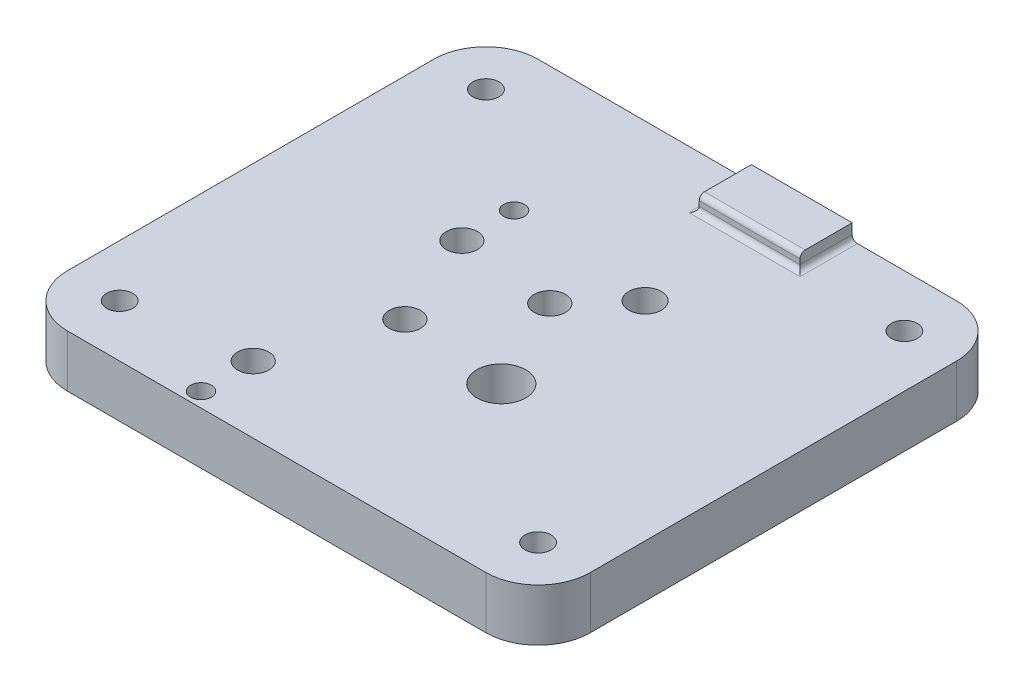
SolidWorks part; units mm, degrees
ref_plane "Front" through (0, 0, 0) normal (0, 0, 1) x (1, 0, 0)
ref_plane "Top" through (0, 0, 0) normal (0, 1, 0) x (1, 0, 0)
ref_plane "Right" through (0, 0, 0) normal (1, 0, 0) x (0, 0, -1)
sketch "Sketch2" plane through (0, 0, 0) normal (0, 1, 0) x (1, 0, 0)
  line L0 (114.3, 127) -> (190.5, 76.2)
  line L1 (114.3, -127) -> (-114.3, -127)
  line L2 (190.5, -76.2) -> (190.5, 76.2)
  line L3 (114.3, 127) -> (-114.3, 127)
  line L4 (-190.5, -76.2) -> (-190.5, 76.2)
  line L5 (190.5, -127) -> (-190.5, 127) construction
  line L6 (190.5, 127) -> (-190.5, -127) construction
  line L7 (190.5, -76.2) -> (114.3, -127)
  line L8 (-114.3, 127) -> (-190.5, 76.2)
  line L9 (-190.5, -76.2) -> (-114.3, -127)
  point P0 (0, 0)
  dimension "D1" = 254
  dimension "D2" = 381
  dimension "D3" = 50.8
  dimension "D4" = 76.2
  dimension "D5" = 76.2
  dimension "D6" = 50.8
  dimension "D7" = 50.8
  dimension "D8" = 76.2
  dimension "D9" = 50.8
  dimension "D10" = 76.2
  dimension "D11" = 228.6
extrude "Boss-Extrude1" add sketch "Sketch2" along normal mid plane 25.4 contours L3 L8 L4 L9 L1 L7 L2 L0
sketch "Sketch5" plane through (0, 12.7, 0) normal (0, 1, 0) x (1, 0, 0)
  circle A0 centre (11.9471, 32.7124) radius 7.9375
  line B0 (-988.0529, -37.29) -> (49011.9471, -37.29) construction
  line B1 (11.9471, -1037.29) -> (11.9471, 48962.71) construction
  circle B2 centre (11.9471, -37.29) radius 25.0063
  circle B3 centre (11.9471, -37.29) radius 11.9126
  arc B4 (29.8046, 15.2073) -> (-12.1051, 39.5537) centre (11.9471, 32.7124) ccw
  arc B5 (29.8046, 15.2073) -> (29.8046, -19.785) centre (47.653, -2.2888) ccw
  arc B6 (-62.9039, -5.1545) -> (-35.018, -60.2135) centre (-58.0553, -37.29) ccw
  arc B7 (-2.6807, -57.5716) -> (-35.018, -60.2135) centre (-17.3011, -77.8429) ccw
  circle B8 centre (-58.0553, -37.29) radius 7.9375
  arc B9 (11.9471, 32.7124) -> (-58.0553, -37.29) centre (11.9471, -37.29) ccw construction
  arc B10 (-62.9039, -5.1545) -> (-12.1051, 39.5537) centre (-72.2297, 56.6554) ccw
  circle B11 centre (11.9471, 32.7124) radius 5.9563
  dimension "D1" = 15.875
sketch_block_instance "Block-block-1"
sketch_block "Block1" parameters "D1"=50.0126, "D2"=23.8252, "D3"=50.0126, "D4"=49.9872, "D6"=15.875, "D7"=64.9986, "D8"=49.9872, "D9"=125.0188, "D10"=11.9126, "D5"=70.0024
extrude "Cut-Extrude3" cut sketch "Sketch5" against normal through all contours B3 | A0 B11 | B11
sketch "Sketch6" plane through (0, 12.7, 0) normal (0, 1, 0) x (1, 0, 0)
  line L0 (-30.9314, 9.7311) -> (-153.4869, 148.9822) construction
  line L1 (-141.3546, 108.5187) -> (113.1534, 108.5187)
  line L2 (-141.3546, 108.5187) -> (-141.3546, -120.5893)
  line L3 (-141.3546, -120.5893) -> (113.1534, -120.5893)
  line L4 (113.1534, 108.5187) -> (113.1534, -120.5893)
  line L5 (-153.4869, 148.9822) -> (111.8664, -152.52) construction
  line L6 (11.9471, -37.29) -> (11.9471, 142.185) construction
  line L7 (11.9471, 142.185) -> (11.9471, -141.8142) construction
  line L8 (-58.0553, -37.29) -> (-206.7494, -37.29) construction
  line L9 (-206.7494, -37.29) -> (209.5432, -37.29) construction
  line L10 (-115.9546, 108.5187) -> (-141.3546, 83.1187)
  line L11 (87.7534, 108.5187) -> (113.1534, 83.1187)
  line L12 (-141.3546, -95.1893) -> (-115.9546, -120.5893)
  line L13 (113.1534, -95.1893) -> (87.7534, -120.5893)
  line L14 (114.3, 127) -> (-114.3, 127) construction
  line L15 (114.3, 127) -> (190.5, 76.2) construction
  line L16 (190.5, -76.2) -> (190.5, 76.2) construction
  line L17 (190.5, -76.2) -> (114.3, -127) construction
  line L18 (114.3, -127) -> (-114.3, -127) construction
  line L19 (-190.5, -76.2) -> (-114.3, -127) construction
  line L20 (-190.5, -76.2) -> (-190.5, 76.2) construction
  line L21 (-114.3, 127) -> (-190.5, 76.2) construction
  line L22 (114.3, 127) -> (-114.3, 127)
  line L23 (114.3, 127) -> (190.5, 76.2)
  line L24 (190.5, -76.2) -> (190.5, 76.2)
  line L25 (190.5, -76.2) -> (114.3, -127)
  line L26 (114.3, -127) -> (-114.3, -127)
  line L27 (-190.5, -76.2) -> (-114.3, -127)
  line L28 (-190.5, -76.2) -> (-190.5, 76.2)
  line L29 (-114.3, 127) -> (-190.5, 76.2)
  arc A0 (29.8046, 15.2073) -> (29.8046, -19.785) centre (47.653, -2.2888) ccw construction
  arc A1 (29.8046, 15.2073) -> (-12.1051, 39.5537) centre (11.9471, 32.7124) ccw construction
  arc A2 (-62.9039, -5.1545) -> (-12.1051, 39.5537) centre (-72.2297, 56.6554) ccw construction
  arc A3 (-62.9039, -5.1545) -> (-35.018, -60.2135) centre (-58.0553, -37.29) ccw construction
  arc A4 (-2.6807, -57.5716) -> (-35.018, -60.2135) centre (-17.3011, -77.8429) ccw construction
  circle A5 centre (11.9471, -37.29) radius 11.9126 construction
  circle A6 centre (11.9471, -37.29) radius 25.0063 construction
  circle A7 centre (11.9471, 32.7124) radius 5.9563 construction
  circle A8 centre (-58.0553, -37.29) radius 7.9375 construction
  arc A9 (29.8046, 15.2073) -> (29.8046, -19.785) centre (47.653, -2.2888) ccw
  arc A10 (29.8046, 15.2073) -> (-12.1051, 39.5537) centre (11.9471, 32.7124) ccw
  arc A11 (-62.9039, -5.1545) -> (-12.1051, 39.5537) centre (-72.2297, 56.6554) ccw
  arc A12 (-62.9039, -5.1545) -> (-35.018, -60.2135) centre (-58.0553, -37.29) ccw
  arc A13 (-2.6807, -57.5716) -> (-35.018, -60.2135) centre (-17.3011, -77.8429) ccw
  circle A14 centre (11.9471, -37.29) radius 11.9126
  circle A15 centre (11.9471, -37.29) radius 25.0063
  circle A16 centre (11.9471, 32.7124) radius 5.9563
  circle A17 centre (-58.0553, -37.29) radius 7.9375
  point P26 (11.9471, 57.7187)
  point P32 (-90.5546, -37.29)
  point P33 (-58.0553, -69.7893)
  point P34 (36.9534, 32.7124)
  line M10 (190.5, 76.2) -> (114.3, 127)
  line M11 (114.3, 127) -> (-114.3, 127)
  line M12 (-114.3, 127) -> (-190.5, 76.2)
  line M13 (-190.5, 76.2) -> (-190.5, -76.2)
  line M14 (-190.5, -76.2) -> (-114.3, -127)
  line M15 (-114.3, -127) -> (114.3, -127)
  line M16 (114.3, -127) -> (190.5, -76.2)
  line M17 (190.5, -76.2) -> (190.5, 76.2)
  dimension "D1" = 50.8
  dimension "D2" = 50.8
  dimension "D3" = 76.2
  dimension "D4" = 50.8
  dimension "D5" = 25.4
  dimension "D6" = 25.4
  dimension "D7" = 25.4
  dimension "D8" = 25.4
  dimension "D9" = 25.4
  dimension "D10" = 25.4
  dimension "D11" = 25.4
  dimension "D12" = 25.4
extrude "Cut-Extrude4" cut sketch "Sketch6" against normal through all contours L1 L4 L3 L2 M17 M10 M11 M12 M13 M14 M15 M16 | L1 L11 L4 | L10 L1 L2 | L12 L2 L3 | L4 L13 L3
sketch "Sketch7" plane through (0, -12.7, 0) normal (0, -1, 0) x (1, 0, 0)
  line L7 (100.4534, 89.9288) -> (82.4929, 107.8893)
  line L9 (100.4534, 89.9288) -> (82.4929, 107.8893)
  line L12 (82.4929, 107.8893) -> (-110.6941, 107.8893)
  line L14 (-110.6941, 107.8893) -> (-128.6546, 89.9288)
  line L15 (-110.6941, 107.8893) -> (-128.6546, 89.9288)
  line L16 (-115.9546, 120.5893) -> (87.7534, 120.5893) construction
  line L17 (82.4929, 107.8893) -> (-110.6941, 107.8893)
  line L18 (-141.3546, -83.1187) -> (-141.3546, 95.1893) construction
  line L19 (113.1534, -83.1187) -> (113.1534, 95.1893) construction
  line L20 (-115.9546, -108.5187) -> (87.7534, -108.5187) construction
  line L24 (-128.6546, 89.9288) -> (-128.6546, -77.8581)
  line L25 (-128.6546, -77.8581) -> (-110.6941, -95.8187)
  line L26 (-110.6941, -95.8187) -> (82.4929, -95.8187)
  line L27 (82.4929, -95.8187) -> (100.4534, -77.8581)
  line L28 (100.4534, -77.8581) -> (100.4534, 89.9288)
  line L32 (-128.6546, 89.9288) -> (-128.6546, -77.8581)
  line L33 (-128.6546, -77.8581) -> (-110.6941, -95.8187)
  line L34 (-110.6941, -95.8187) -> (82.4929, -95.8187)
  line L35 (82.4929, -95.8187) -> (100.4534, -77.8581)
  line L36 (100.4534, -77.8581) -> (100.4534, 89.9288)
  circle A0 centre (87.7534, 95.1893) radius 12.7
  circle A1 centre (-115.9546, 95.1893) radius 12.7
  circle A2 centre (87.7534, -83.1187) radius 12.7
  circle A3 centre (-115.9546, -83.1187) radius 12.7
  point P0 (-115.9546, 95.1893)
  point P1 (87.7534, 95.1893)
  point P3 (87.7534, -83.1187)
  point P4 (-115.9546, -83.1187)
  dimension "D10" = 25.4
  dimension "D11" = 25.4
  dimension "D12" = 25.4
  dimension "D13" = 25.4
  dimension "D2" = 25.4
  dimension "D3" = 25.4
  dimension "D4" = 25.4
  dimension "D5" = 25.4
  dimension "D6" = 25.4
  dimension "D7" = 25.4
  dimension "D8" = 25.4
  dimension "D9" = 25.4
  dimension "D1" = 12.7
extrude "Cut-Extrude5" cut sketch "Sketch7" against normal blind 7.5057 contours L9 A0 | L9 A0 | L15 A1 | L15 A1 | L35 A2 | L35 A2 | L33 A3 | L33 A3
sketch "Sketch8" plane through (0, -5.1943, 0) normal (0, -1, 0) x (1, 0, 0)
  circle A0 centre (-115.9546, 95.1893) radius 6.35
  circle A1 centre (87.7534, 95.1893) radius 6.35
  circle A2 centre (87.7534, -83.1187) radius 6.35
  circle A3 centre (-115.9546, -83.1187) radius 6.35
  dimension "D1" = 12.7
  dimension "D2" = 12.7
  dimension "D3" = 12.7
  dimension "D4" = 12.7
extrude "Cut-Extrude6" cut sketch "Sketch8" against normal through all contours A0 | A1 | A3 | A2
sketch "Sketch9" plane through (0, 12.7, 0) normal (0, 1, 0) x (1, 0, 0)
  line L0 (-115.9546, 108.5187) -> (-141.3546, 83.1187) construction
  line L1 (-141.3546, 83.1187) -> (-141.3546, -95.1893) construction
  line L2 (-141.3546, -95.1893) -> (-115.9546, -120.5893) construction
  line L3 (-115.9546, -120.5893) -> (87.7534, -120.5893) construction
  line L4 (113.1534, -95.1893) -> (87.7534, -120.5893) construction
  line L5 (113.1534, 83.1187) -> (113.1534, -95.1893) construction
  line L6 (87.7534, 108.5187) -> (113.1534, 83.1187) construction
  line L7 (-115.9546, 108.5187) -> (87.7534, 108.5187) construction
  line L8 (-115.9546, 108.5187) -> (-141.3546, 83.1187)
  line L9 (-141.3546, 83.1187) -> (-141.3546, -95.1893)
  line L10 (-141.3546, -95.1893) -> (-115.9546, -120.5893)
  line L11 (-115.9546, -120.5893) -> (87.7534, -120.5893)
  line L12 (113.1534, -95.1893) -> (87.7534, -120.5893)
  line L13 (113.1534, 83.1187) -> (113.1534, -95.1893)
  line L14 (87.7534, 108.5187) -> (113.1534, 83.1187)
  line L15 (-115.9546, 108.5187) -> (87.7534, 108.5187)
  arc A0 (-115.9546, 108.5187) -> (-141.3546, 83.1187) centre (-115.9546, 83.1187) ccw
  arc A1 (-115.9546, -120.5893) -> (-141.3546, -95.1893) centre (-115.9546, -95.1893) cw
  arc A2 (87.7534, -120.5893) -> (113.1534, -95.1893) centre (87.7534, -95.1893) ccw
  arc A3 (113.1534, 83.1187) -> (87.7534, 108.5187) centre (87.7534, 83.1187) ccw
  line M20 (-115.9546, 108.5187) -> (-141.3546, 83.1187)
  line M22 (-141.3546, -95.1893) -> (-115.9546, -120.5893)
  line M24 (87.7534, -120.5893) -> (113.1534, -95.1893)
  line M26 (113.1534, 83.1187) -> (87.7534, 108.5187)
  dimension "D1" = 25.4
extrude "Boss-Extrude2" add sketch "Sketch9" against normal blind 25.4 contours A3 M26 | A0 M20 | A1 M22 | A2 M24
sketch "Sketch10" plane through (0, 12.7, 0) normal (0, 1, 0) x (1, 0, 0)
  line L0 (-12.1051, 39.5537) -> (-12.1051, 108.5187) construction
  line L1 (-115.9546, 108.5187) -> (87.7534, 108.5187) construction
  line L2 (36.9534, 32.7124) -> (36.9534, 108.5187) construction
  line L3 (-62.9039, -5.1545) -> (-141.3546, -6.0353) construction
  line L4 (-141.3546, 83.1187) -> (-141.3546, -95.1893) construction
  line L5 (-58.0553, -69.7893) -> (-141.3546, -69.7893) construction
  line L6 (11.9471, 32.7124) -> (11.9471, 108.5187) construction
  line L7 (-19.9299, 108.5187) -> (-19.9299, 39.5537) construction
  line L8 (43.9511, 108.5187) -> (43.9511, 32.7124) construction
  line L10 (-12.1051, 108.5187) -> (36.9534, 108.5187)
  line L11 (-12.1051, 108.5187) -> (-12.1051, 83.1187)
  line L12 (-12.1051, 83.1187) -> (36.9534, 83.1187)
  line L13 (36.9534, 108.5187) -> (36.9534, 83.1187)
  arc A0 (29.8046, 15.2073) -> (29.8046, -19.785) centre (47.653, -2.2888) ccw construction
  arc A1 (29.8046, 15.2073) -> (-12.1051, 39.5537) centre (11.9471, 32.7124) ccw construction
  arc A2 (-62.9039, -5.1545) -> (-12.1051, 39.5537) centre (-72.2297, 56.6554) ccw construction
  arc A3 (-62.9039, -5.1545) -> (-35.018, -60.2135) centre (-58.0553, -37.29) ccw construction
  arc A4 (-2.6807, -57.5716) -> (-35.018, -60.2135) centre (-17.3011, -77.8429) ccw construction
  circle A5 centre (11.9471, -37.29) radius 11.9126 construction
  circle A6 centre (11.9471, -37.29) radius 25.0063 construction
  circle A7 centre (11.9471, 32.7124) radius 5.9563 construction
  circle A8 centre (-58.0553, -37.29) radius 7.9375 construction
  arc A9 (29.8046, 15.2073) -> (29.8046, -19.785) centre (47.653, -2.2888) ccw
  arc A10 (29.8046, 15.2073) -> (-12.1051, 39.5537) centre (11.9471, 32.7124) ccw
  arc A11 (-62.9039, -5.1545) -> (-12.1051, 39.5537) centre (-72.2297, 56.6554) ccw
  arc A12 (-62.9039, -5.1545) -> (-35.018, -60.2135) centre (-58.0553, -37.29) ccw
  arc A13 (-2.6807, -57.5716) -> (-35.018, -60.2135) centre (-17.3011, -77.8429) ccw
  circle A14 centre (11.9471, -37.29) radius 11.9126
  circle A15 centre (11.9471, -37.29) radius 25.0063
  circle A16 centre (11.9471, 32.7124) radius 5.9563
  circle A17 centre (-58.0553, -37.29) radius 7.9375
  line M10 (87.7534, 108.5187) -> (-115.9546, 108.5187)
  dimension "D1" = 31.877
  dimension "D2" = 32.004
  dimension "D3" = 25.4
  dimension "D4" = 49.0586
extrude "Boss-Extrude3" add sketch "Sketch10" along normal blind 7.493 contours L13 L11 L12 M10
fillet "Fillet1" radius 2.54 4 edges at (12.4242, 12.7, -83.1187) (12.4242, 20.193, -83.1187) (36.9534, 12.7, -95.8187) (-12.1051, 12.7, -95.8187)
sketch "Sketch11" plane through (0, 0, -108.5187) normal (0, 0, -1) x (-1, 0, 0)
  line L0 (-12.4242, 20.193) -> (-12.4242, -12.7) construction
  line L1 (-36.9534, 20.193) -> (12.1051, 20.193) construction
  line L2 (115.9546, -12.7) -> (-87.7534, -12.7) construction
  line L3 (-25.1242, 20.193) -> (-25.1242, -12.7) construction
  line L4 (-25.1242, 3.7465) -> (-48.5067, 3.7465) construction
  line L5 (-48.5067, 3.7465) -> (17.9345, 3.7465) construction
  circle A0 centre (-25.1242, 3.7465) radius 5.08
  circle A1 centre (0.2758, 3.7465) radius 5.08
  dimension "D2" = 10.16
  dimension "D1" = 12.7
extrude "Cut-Extrude7" cut sketch "Sketch11" against normal blind 17.78 contours A1 | A0
sketch "Sketch12" plane through (0, 12.7, 0) normal (0, 1, 0) x (1, 0, 0)
  line L0 (-10.1781, 8.4387) -> (11.9471, -37.29) construction
  line L1 (11.9471, -37.29) -> (-38.7177, -33.5867) construction
  arc A0 (29.8046, 15.2073) -> (29.8046, -19.785) centre (47.653, -2.2888) ccw construction
  circle A1 centre (11.9471, 32.7124) radius 7.9375
  circle A2 centre (11.9471, 32.7124) radius 7.9375
  arc A3 (29.8046, 15.2073) -> (-12.1051, 39.5537) centre (11.9471, 32.7124) ccw construction
  arc A4 (-62.9039, -5.1545) -> (-12.1051, 39.5537) centre (-72.2297, 56.6554) ccw construction
  arc A5 (-62.9039, -5.1545) -> (-35.018, -60.2135) centre (-58.0553, -37.29) ccw construction
  arc A6 (-2.6807, -57.5716) -> (-35.018, -60.2135) centre (-17.3011, -77.8429) ccw construction
  circle A7 centre (11.9471, -37.29) radius 11.9126 construction
  circle A8 centre (11.9471, -37.29) radius 25.0063 construction
  circle A9 centre (11.9471, 32.7124) radius 5.9563 construction
  circle A10 centre (-58.0553, -37.29) radius 7.9375 construction
  arc A11 (29.8046, 15.2073) -> (29.8046, -19.785) centre (47.653, -2.2888) ccw
  arc A12 (29.8046, 15.2073) -> (-12.1051, 39.5537) centre (11.9471, 32.7124) ccw
  arc A13 (-62.9039, -5.1545) -> (-12.1051, 39.5537) centre (-72.2297, 56.6554) ccw
  arc A14 (-62.9039, -5.1545) -> (-35.018, -60.2135) centre (-58.0553, -37.29) ccw
  arc A15 (-2.6807, -57.5716) -> (-35.018, -60.2135) centre (-17.3011, -77.8429) ccw
  circle A16 centre (11.9471, -37.29) radius 11.9126
  circle A17 centre (11.9471, -37.29) radius 25.0063
  circle A18 centre (11.9471, 32.7124) radius 5.9563
  circle A19 centre (-58.0553, -37.29) radius 7.9375
  circle A20 centre (11.9471, -37.29) radius 50.8
  circle A21 centre (-10.1781, 8.4387) radius 7.62
  circle A22 centre (-38.7177, -33.5867) radius 7.62
  dimension "D2" = 101.6
  dimension "D3" = 15.24
  dimension "D4" = 15.24
  dimension "D5" = 60
  dimension "D1" = 0
extrude "Cut-Extrude8" cut sketch "Sketch12" against normal through all contours A20 A22 | A20 A22 | A20 A21 | A20 A21
sketch "Sketch13" plane through (0, 12.7, 0) normal (0, 1, 0) x (1, 0, 0)
  circle A0 centre (11.9471, 32.7124) radius 7.9375 construction
  circle A1 centre (11.9471, 32.7124) radius 7.9375
sketch "Sketch14" plane through (0, 12.7, 0) normal (0, 1, 0) x (1, 0, 0)
  arc A0 (29.8046, 15.2073) -> (29.8046, -19.785) centre (47.653, -2.2888) ccw construction
  circle A1 centre (11.9471, 32.7124) radius 7.9375
  circle A2 centre (11.9471, 32.7124) radius 7.9375
  arc A3 (29.8046, 15.2073) -> (-12.1051, 39.5537) centre (11.9471, 32.7124) ccw construction
  arc A4 (-62.9039, -5.1545) -> (-12.1051, 39.5537) centre (-72.2297, 56.6554) ccw construction
  arc A5 (-62.9039, -5.1545) -> (-35.018, -60.2135) centre (-58.0553, -37.29) ccw construction
  arc A6 (-2.6807, -57.5716) -> (-35.018, -60.2135) centre (-17.3011, -77.8429) ccw construction
  circle A7 centre (11.9471, -37.29) radius 11.9126 construction
  circle A8 centre (11.9471, -37.29) radius 25.0063 construction
  circle A9 centre (11.9471, 32.7124) radius 5.9563 construction
  arc A11 (29.8046, 15.2073) -> (29.8046, -19.785) centre (47.653, -2.2888) ccw
  arc A12 (29.8046, 15.2073) -> (-12.1051, 39.5537) centre (11.9471, 32.7124) ccw
  arc A13 (-62.9039, -5.1545) -> (-12.1051, 39.5537) centre (-72.2297, 56.6554) ccw
  arc A14 (-62.9039, -5.1545) -> (-35.018, -60.2135) centre (-58.0553, -37.29) ccw
  arc A15 (-2.6807, -57.5716) -> (-35.018, -60.2135) centre (-17.3011, -77.8429) ccw
  circle A16 centre (11.9471, -37.29) radius 11.9126
  circle A17 centre (11.9471, -37.29) radius 25.0063
  circle A18 centre (11.9471, 32.7124) radius 5.9563
  circle A20 centre (-58.0553, -37.29) radius 5.08
  dimension "D2" = 10.16
  dimension "D1" = 0
extrude "Boss-Extrude4" add sketch "Sketch14" against normal blind 50.8 contours A20
sketch "Sketch16" plane through (0, 12.7, 0) normal (0, 1, 0) x (1, 0, 0)
  line L0 (-58.0553, -37.29) -> (-58.0553, 50.4641) construction
  line L1 (-58.0553, 50.4641) -> (-58.0553, -120.5893) construction
  line L2 (-115.9546, -120.5893) -> (87.7534, -120.5893) construction
  arc A0 (29.8046, 15.2073) -> (29.8046, -19.785) centre (47.653, -2.2888) ccw construction
  circle A1 centre (11.9471, 32.7124) radius 7.9375
  circle A2 centre (11.9471, 32.7124) radius 7.9375
  arc A3 (29.8046, 15.2073) -> (-12.1051, 39.5537) centre (11.9471, 32.7124) ccw construction
  arc A4 (-62.9039, -5.1545) -> (-12.1051, 39.5537) centre (-72.2297, 56.6554) ccw construction
  arc A5 (-62.9039, -5.1545) -> (-35.018, -60.2135) centre (-58.0553, -37.29) ccw construction
  arc A6 (-2.6807, -57.5716) -> (-35.018, -60.2135) centre (-17.3011, -77.8429) ccw construction
  circle A7 centre (11.9471, -37.29) radius 11.9126 construction
  circle A8 centre (11.9471, -37.29) radius 25.0063 construction
  circle A9 centre (11.9471, 32.7124) radius 5.9563 construction
  circle A10 centre (-58.0553, -37.29) radius 7.9375 construction
  arc A11 (29.8046, 15.2073) -> (29.8046, -19.785) centre (47.653, -2.2888) ccw
  arc A12 (29.8046, 15.2073) -> (-12.1051, 39.5537) centre (11.9471, 32.7124) ccw
  arc A13 (-62.9039, -5.1545) -> (-12.1051, 39.5537) centre (-72.2297, 56.6554) ccw
  arc A14 (-62.9039, -5.1545) -> (-35.018, -60.2135) centre (-58.0553, -37.29) ccw
  arc A15 (-2.6807, -57.5716) -> (-35.018, -60.2135) centre (-17.3011, -77.8429) ccw
  circle A16 centre (11.9471, -37.29) radius 11.9126
  circle A17 centre (11.9471, -37.29) radius 25.0063
  circle A18 centre (11.9471, 32.7124) radius 5.9563
  circle A19 centre (-58.0553, -37.29) radius 7.9375
  circle A20 centre (-58.0553, 13.51) radius 7.62
  circle A21 centre (-58.0553, -88.09) radius 7.62
  dimension "D2" = 15.24
  dimension "D3" = 15.24
  dimension "D4" = 50.8
  dimension "D5" = 50.8
  dimension "D1" = 0
extrude "Cut-Extrude10" cut sketch "Sketch16" against normal through all contours A20 | A21
sketch "Sketch17" plane through (0, 12.7, 0) normal (0, 1, 0) x (1, 0, 0)
  line L0 (-58.0553, -37.29) -> (-58.0553, 92.6932) construction
  line L1 (-58.0553, 92.6932) -> (-58.0553, -120.5893) construction
  line L2 (-115.9546, -120.5893) -> (87.7534, -120.5893) construction
  arc A0 (29.8046, 15.2073) -> (29.8046, -19.785) centre (47.653, -2.2888) ccw construction
  circle A1 centre (11.9471, 32.7124) radius 7.9375
  circle A2 centre (11.9471, 32.7124) radius 7.9375
  arc A3 (29.8046, 15.2073) -> (-12.1051, 39.5537) centre (11.9471, 32.7124) ccw construction
  arc A4 (-62.9039, -5.1545) -> (-12.1051, 39.5537) centre (-72.2297, 56.6554) ccw construction
  arc A5 (-62.9039, -5.1545) -> (-35.018, -60.2135) centre (-58.0553, -37.29) ccw construction
  arc A6 (-2.6807, -57.5716) -> (-35.018, -60.2135) centre (-17.3011, -77.8429) ccw construction
  circle A7 centre (11.9471, -37.29) radius 11.9126 construction
  circle A8 centre (11.9471, -37.29) radius 25.0063 construction
  circle A9 centre (11.9471, 32.7124) radius 5.9563 construction
  circle A10 centre (-58.0553, -37.29) radius 7.9375 construction
  arc A11 (29.8046, 15.2073) -> (29.8046, -19.785) centre (47.653, -2.2888) ccw
  arc A12 (29.8046, 15.2073) -> (-12.1051, 39.5537) centre (11.9471, 32.7124) ccw
  arc A13 (-62.9039, -5.1545) -> (-12.1051, 39.5537) centre (-72.2297, 56.6554) ccw
  arc A14 (-62.9039, -5.1545) -> (-35.018, -60.2135) centre (-58.0553, -37.29) ccw
  arc A15 (-2.6807, -57.5716) -> (-35.018, -60.2135) centre (-17.3011, -77.8429) ccw
  circle A16 centre (11.9471, -37.29) radius 11.9126
  circle A17 centre (11.9471, -37.29) radius 25.0063
  circle A18 centre (11.9471, 32.7124) radius 5.9563
  circle A19 centre (-58.0553, -37.29) radius 7.9375
  circle A20 centre (-58.0553, 13.51) radius 7.62 construction
  circle A21 centre (-58.0553, 13.51) radius 7.62
  circle A22 centre (-58.0553, -88.09) radius 7.62 construction
  circle A23 centre (-58.0553, -88.09) radius 7.62
  circle A24 centre (-58.0553, 38.91) radius 5.08
  circle A25 centre (-58.0553, -113.49) radius 5.08
  dimension "D2" = 10.16
  dimension "D3" = 10.16
  dimension "D4" = 25.4
  dimension "D5" = 25.4
  dimension "D1" = 0
extrude "Cut-Extrude11" cut sketch "Sketch17" against normal through all contours A24 | A25
